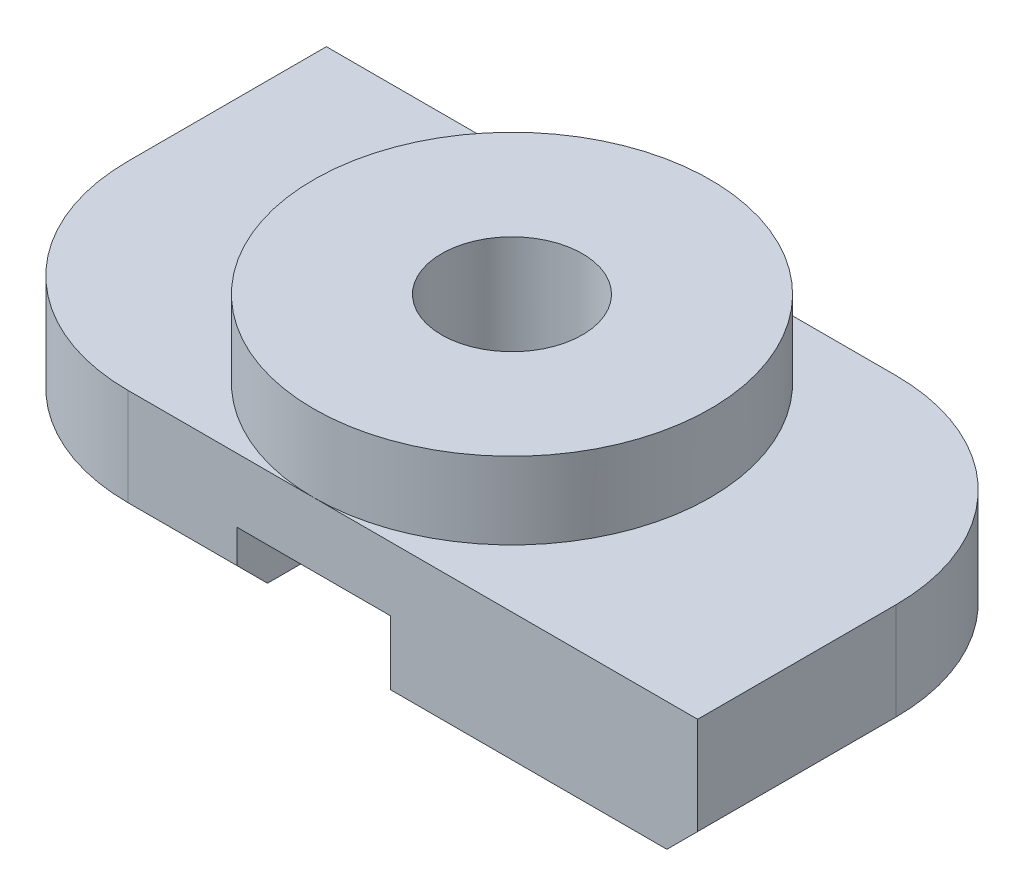
SolidWorks part; units mm, degrees
ref_plane "Front Plane" through (0, 0, 0) normal (0, 0, 1) x (1, 0, 0)
ref_plane "Top Plane" through (0, 0, 0) normal (0, 1, 0) x (1, 0, 0)
ref_plane "Right Plane" through (0, 0, 0) normal (1, 0, 0) x (0, 0, -1)
sketch "Sketch1" plane through (0, 0, 0) normal (0, 1, 0) x (1, 0, 0)
  line L1 (0, 0) -> (15.24, 0)
  line L2 (0, 0) -> (0, 7.874)
  line L3 (0, 7.874) -> (15.24, 7.874)
  line L4 (15.24, 0) -> (15.24, 7.874)
  dimension "D1" = 15.24
  dimension "D2" = 7.874
extrude "Boss-Extrude1" add sketch "Sketch1" along normal blind 2.54
sketch "Sketch2" plane through (0, 2.54, 0) normal (0, 1, 0) x (1, 0, 0)
  line L0 (7.62, 7.874) -> (7.62, 0) construction
  line L1 (15.24, 7.874) -> (0, 7.874) construction
  line L2 (0, 0) -> (15.24, 0) construction
  line L3 (0, 3.937) -> (15.24, 3.937) construction
  line L4 (0, 7.874) -> (0, 0) construction
  line L5 (15.24, 0) -> (15.24, 7.874) construction
  circle A0 centre (7.62, 3.937) radius 3.937
extrude "Boss-Extrude2" add sketch "Sketch2" along normal blind 1.524
sketch "Sketch3" plane through (0, 4.064, 0) normal (0, 1, 0) x (1, 0, 0)
  circle A0 centre (7.62, 3.937) radius 1.397
extrude "Cut-Extrude1" cut sketch "Sketch3" against normal through all
fillet "Fillet1" radius 3.937 2 edges at (15.24, 1.27, -7.874) (0, 1.27, 0)
sketch "Sketch4" plane through (0, 0, 0) normal (0, -1, 0) x (1, 0, 0)
  line L0 (3.937, 0) -> (15.24, 0) construction
  line L1 (6.096, 0) -> (9.144, 0)
  line L2 (6.096, 0) -> (6.096, -7.874)
  line L3 (6.096, -7.874) -> (9.144, -7.874)
  line L4 (9.144, 0) -> (9.144, -7.874)
  line L5 (11.303, -7.874) -> (0, -7.874) construction
  circle A0 centre (7.62, -3.937) radius 1.397 construction
  dimension "D1" = 3.048
  dimension "D2" = 1.524
extrude "Cut-Extrude2" cut sketch "Sketch4" against normal blind 1.27
chamfer "Chamfer1" distance 0.6096 angle 45 6 edges at (10.2235, 0, -7.874) (14.0869, 0, -6.7209) (15.24, 0, -1.9685) (5.0165, 0, 0) (1.1531, 0, -1.1531) (0, 0, -5.9055)
